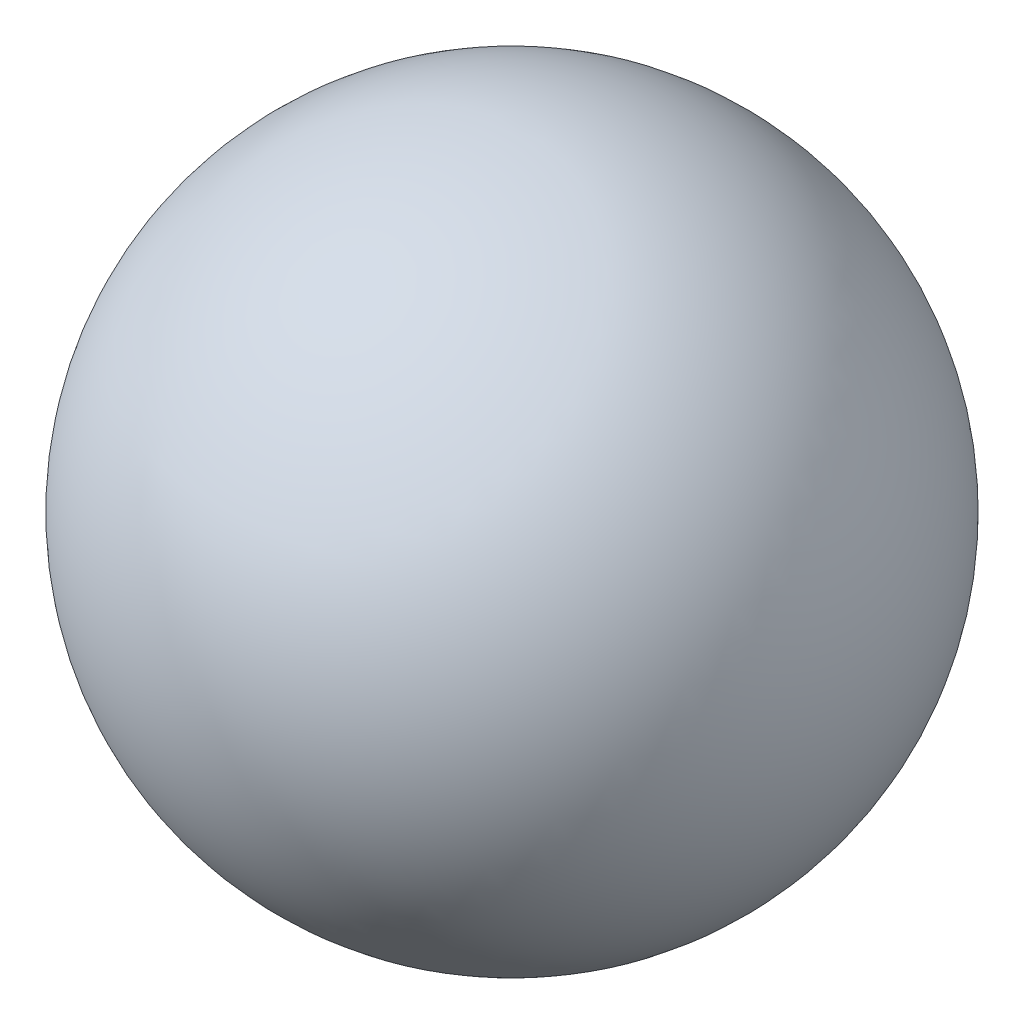
SolidWorks part; units mm, degrees
ref_plane "Plan de face" through (0, 0, 0) normal (0, 0, 1) x (1, 0, 0)
ref_plane "Plan de dessus" through (0, 0, 0) normal (0, 1, 0) x (1, 0, 0)
ref_plane "Plan de droite" through (0, 0, 0) normal (1, 0, 0) x (0, 0, -1)
sketch "Esquisse1" plane through (0, 0, 0) normal (0, 0, 1) x (1, 0, 0)
  line L0 (0, 0) -> (0, 3.0601) construction
  line L1 (0, -7) -> (0, 7)
  arc A0 (0, -7) -> (0, 7) centre (0, 0) ccw
  dimension "D1" = 7
revolve "Révolution1" add sketch "Esquisse1" angle 360 about L0
